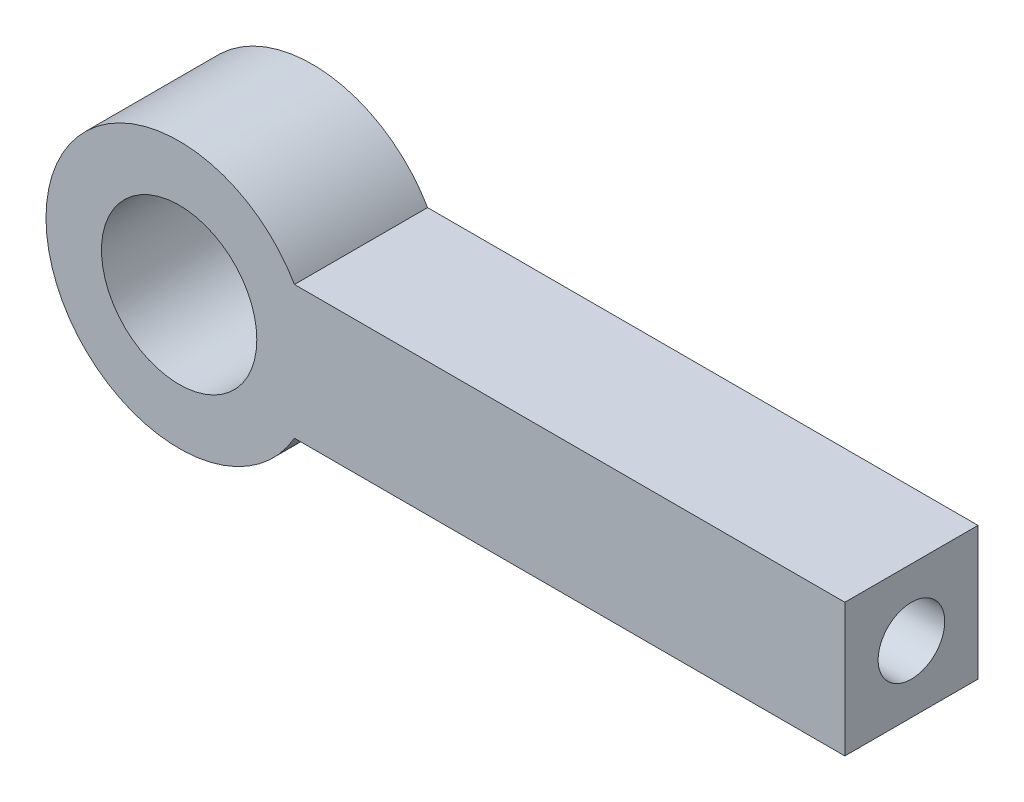
SolidWorks part; units mm, degrees
ref_plane "Top Plane" through (0, 0, 0) normal (0, 0, 1) x (1, 0, 0)
ref_plane "Right Plane" through (0, 0, 0) normal (0, 1, 0) x (1, 0, 0)
ref_plane "Front Plane" through (0, 0, 0) normal (1, 0, 0) x (0, 0, -1)
sketch "Sketch1" plane through (0, 0, 0) normal (0, 0, 1) x (1, 0, 0)
  line L0 (0, 0) -> (30, 0) construction
  line L1 (5.1962, -3) -> (30, -3)
  line L2 (30, -3) -> (30, 3)
  line L3 (5.1962, 3) -> (30, 3)
  line L4 (3.1623, -1.5) -> (30, -1.5) construction
  line L5 (3.1623, 1.5) -> (30, 1.5) construction
  circle A0 centre (0, 0) radius 3.5 construction
  arc A1 (5.1962, 3) -> (5.1962, -3) centre (0, 0) ccw
  dimension "D1" = 7
  dimension "D2" = 12
  dimension "D3" = 6
  dimension "D4" = 3
  dimension "D5" = 30
extrude "Boss-Extrude1" add sketch "Sketch1" along normal mid plane 6
sketch "Sketch10" plane through (0, 0, 3) normal (0, 0, 1) x (1, 0, 0)
  circle A0 centre (0, 0) radius 3.5
  circle A1 centre (0, 0) radius 3.5 construction
extrude "Cut-Extrude1" cut sketch "Sketch10" against normal through all both and the other way through all
sketch "Sketch11" plane through (30, 0, 0) normal (1, 0, 0) x (0, 0, -1)
  line L0 (0, 6) -> (0, -6) construction
  circle A0 centre (0, 0) radius 1.5
  dimension "D1" = 3
extrude "Cut-Extrude2" cut sketch "Sketch11" against normal blind 20
